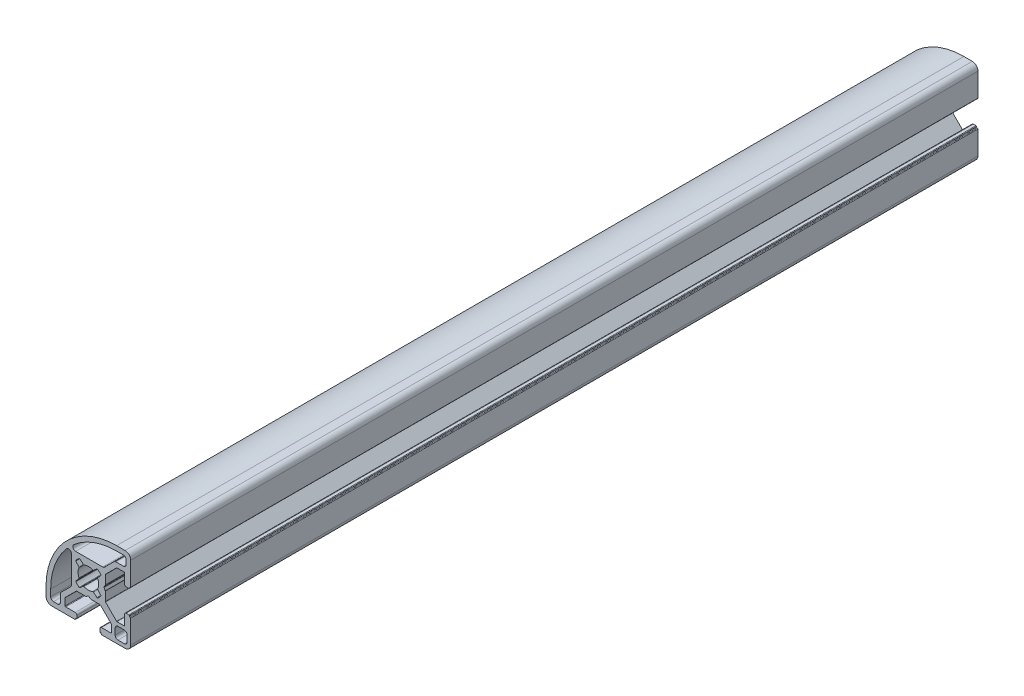
SolidWorks part; units mm, degrees
ref_plane "Front Plane" through (0, 0, 0) normal (0, 0, 1) x (1, 0, 0)
ref_plane "Top Plane" through (0, 0, 0) normal (0, 1, 0) x (1, 0, 0)
ref_plane "Right Plane" through (0, 0, 0) normal (1, 0, 0) x (0, 0, -1)
sketch "Sketch1" plane through (0, 0, 0) normal (0, 0, 1) x (1, 0, 0)
  line L0 (-5.9955, -5.0479) -> (-5.9955, 4.5146)
  line L1 (-9.6071, -9.0737) -> (-6.2884, -5.755)
  line L2 (-9.9, -12.35) -> (-9.9, -9.7808)
  line L3 (-13.35, -12.35) -> (-13.35, -10)
  line L4 (-10.9, -13.35) -> (-12.35, -13.35)
  line L5 (13.35, 10.9) -> (13.35, 12.35)
  line L6 (12.35, 13.35) -> (10, 13.35)
  line L7 (12.35, 9.9) -> (9.7808, 9.9)
  line L8 (9.0737, 9.6071) -> (5.755, 6.2884)
  line L9 (5.0479, 5.9955) -> (-4.5146, 5.9955)
  line L10 (13.7, -10.5) -> (13.7, -12.7)
  line L11 (5.9777, -0.8536) -> (5.5426, -0.1)
  line L12 (5.9777, 0.8536) -> (5.5426, 0.1)
  line L13 (6.0045, -4.1216) -> (6.0045, -0.9536)
  line L14 (6.0045, 4.1216) -> (6.0045, 0.9536)
  line L15 (-3.3344, 1.7592) -> (-4.4052, 3.0354)
  line L16 (-1.7592, 3.3344) -> (-3.0354, 4.4052)
  line L17 (1.7592, 3.3344) -> (3.0354, 4.4052)
  line L18 (3.3344, 1.7592) -> (4.4052, 3.0354)
  line L19 (15, 4.75) -> (15, 13)
  line L20 (13, 15) -> (10, 15)
  line L21 (14.5, 4.35) -> (14.5, 4.25)
  line L22 (14.3, 4.05) -> (13.4, 4.05)
  line L23 (12.8, 4.65) -> (12.8, 8.05)
  line L24 (14.7, 4.55) -> (14.8, 4.55)
  line L25 (12.6, 8.25) -> (10.1328, 8.25)
  line L26 (9.9914, 8.1914) -> (6.063, 4.263)
  line L27 (8.1914, -9.9914) -> (4.263, -6.063)
  line L28 (8.25, -12.6) -> (8.25, -10.1328)
  line L29 (9.9914, -8.1914) -> (6.063, -4.263)
  line L30 (12.6, -8.25) -> (10.1328, -8.25)
  line L31 (14.7, -4.55) -> (14.8, -4.55)
  line L32 (12.8, -4.65) -> (12.8, -8.05)
  line L33 (14.3, -4.05) -> (13.4, -4.05)
  line L34 (14.5, -4.35) -> (14.5, -4.25)
  line L35 (4.65, -12.8) -> (8.05, -12.8)
  line L36 (4.05, -14.3) -> (4.05, -13.4)
  line L37 (4.35, -14.5) -> (4.25, -14.5)
  line L38 (4.55, -14.8) -> (4.55, -14.7)
  line L39 (13, -15) -> (4.75, -15)
  line L40 (15, -4.75) -> (15, -13)
  line L41 (3.3344, -1.7592) -> (4.4052, -3.0354)
  line L42 (1.7592, -3.3344) -> (3.0354, -4.4052)
  line L43 (-1.7592, -3.3344) -> (-3.0354, -4.4052)
  line L44 (-3.3344, -1.7592) -> (-4.4052, -3.0354)
  line L45 (-15, -10) -> (-15, -13)
  line L46 (-13, -15) -> (-4.75, -15)
  line L47 (-4.55, -14.8) -> (-4.55, -14.7)
  line L48 (-4.35, -14.5) -> (-4.25, -14.5)
  line L49 (-4.05, -14.3) -> (-4.05, -13.4)
  line L50 (-4.65, -12.8) -> (-8.05, -12.8)
  line L51 (-8.1914, -9.9914) -> (-4.263, -6.063)
  line L52 (-4.1216, -6.0045) -> (-0.9536, -6.0045)
  line L53 (-0.8536, -5.9777) -> (-0.1, -5.5426)
  line L54 (12.7, -9.5) -> (10.5, -9.5)
  line L55 (9.5, -10.5) -> (9.5, -12.7)
  line L56 (10.5, -13.7) -> (12.7, -13.7)
  line L57 (0.8536, -5.9777) -> (0.1, -5.5426)
  line L58 (4.1216, -6.0045) -> (0.9536, -6.0045)
  line L59 (-8.25, -12.6) -> (-8.25, -10.1328)
  arc A0 (-5.9955, 4.5146) -> (-7.756, 5.164) centre (-6.9955, 4.5146) ccw
  arc A1 (-6.2884, -5.755) -> (-5.9955, -5.0479) centre (-6.9955, -5.0479) ccw
  arc A2 (-7.756, 5.164) -> (-13.35, -10) centre (10, -10) ccw
  arc A3 (-13.35, -12.35) -> (-12.35, -13.35) centre (-12.35, -12.35) ccw
  arc A4 (-10.9, -13.35) -> (-9.9, -12.35) centre (-10.9, -12.35) ccw
  arc A5 (-9.6071, -9.0737) -> (-9.9, -9.7808) centre (-8.9, -9.7808) ccw
  arc A6 (-5.164, 7.756) -> (-4.5146, 5.9955) centre (-4.5146, 6.9955) ccw
  arc A7 (5.0479, 5.9955) -> (5.755, 6.2884) centre (5.0479, 6.9955) ccw
  arc A8 (9.7808, 9.9) -> (9.0737, 9.6071) centre (9.7808, 8.9) ccw
  arc A9 (12.35, 9.9) -> (13.35, 10.9) centre (12.35, 10.9) ccw
  arc A10 (13.35, 12.35) -> (12.35, 13.35) centre (12.35, 12.35) ccw
  arc A11 (10, 13.35) -> (-5.164, 7.756) centre (10, -10) ccw
  arc A12 (-8.1914, -9.9914) -> (-8.25, -10.1328) centre (-8.05, -10.1328) ccw
  arc A13 (-4.1216, -6.0045) -> (-4.263, -6.063) centre (-4.1216, -6.2045) ccw
  arc A14 (-0.9536, -6.0045) -> (-0.8536, -5.9777) centre (-0.9536, -5.8045) ccw
  arc A15 (0.8536, -5.9777) -> (0.9536, -6.0045) centre (0.9536, -5.8045) ccw
  arc A16 (4.263, -6.063) -> (4.1216, -6.0045) centre (4.1216, -6.2045) ccw
  arc A17 (8.25, -10.1328) -> (8.1914, -9.9914) centre (8.05, -10.1328) ccw
  arc A18 (5.9777, 0.8536) -> (6.0045, 0.9536) centre (5.8045, 0.9536) ccw
  arc A19 (6.0045, -0.9536) -> (5.9777, -0.8536) centre (5.8045, -0.9536) ccw
  arc A20 (9.9914, -8.1914) -> (10.1328, -8.25) centre (10.1328, -8.05) ccw
  arc A21 (6.0045, -4.1216) -> (6.063, -4.263) centre (6.2045, -4.1216) ccw
  arc A22 (10.1328, 8.25) -> (9.9914, 8.1914) centre (10.1328, 8.05) ccw
  arc A23 (6.063, 4.263) -> (6.0045, 4.1216) centre (6.2045, 4.1216) ccw
  arc A24 (3.2833, 4.4125) -> (3.0354, 4.4052) centre (3.1639, 4.252) ccw
  arc A25 (4.4052, 3.0354) -> (4.4125, 3.2833) centre (4.252, 3.1639) ccw
  arc A26 (4.4125, -3.2833) -> (4.4052, -3.0354) centre (4.252, -3.1639) ccw
  arc A27 (3.0354, -4.4052) -> (3.2833, -4.4125) centre (3.1639, -4.252) ccw
  arc A28 (-3.2833, -4.4125) -> (-3.0354, -4.4052) centre (-3.1639, -4.252) ccw
  arc A29 (-4.4052, -3.0354) -> (-4.4125, -3.2833) centre (-4.252, -3.1639) ccw
  arc A30 (-4.4125, 3.2833) -> (-4.4052, 3.0354) centre (-4.252, 3.1639) ccw
  arc A31 (-3.0354, 4.4052) -> (-3.2833, 4.4125) centre (-3.1639, 4.252) ccw
  arc A32 (-3.3064, 1.5459) -> (-3.3344, 1.7592) centre (-3.4876, 1.6307) ccw
  arc A33 (-3.3344, -1.7592) -> (-3.3064, -1.5459) centre (-3.4876, -1.6307) ccw
  arc A34 (-1.5459, -3.3064) -> (-1.7592, -3.3344) centre (-1.6307, -3.4876) ccw
  arc A35 (1.7592, -3.3344) -> (1.5459, -3.3064) centre (1.6307, -3.4876) ccw
  arc A36 (3.3064, -1.5459) -> (3.3344, -1.7592) centre (3.4876, -1.6307) ccw
  arc A37 (3.3344, 1.7592) -> (3.3064, 1.5459) centre (3.4876, 1.6307) ccw
  arc A38 (1.5459, 3.3064) -> (1.7592, 3.3344) centre (1.6307, 3.4876) ccw
  arc A39 (-1.7592, 3.3344) -> (-1.5459, 3.3064) centre (-1.6307, 3.4876) ccw
  arc A40 (-1.5459, -3.3064) -> (1.5459, -3.3064) centre (0, 0) ccw
  arc A41 (-3.3064, 1.5459) -> (-3.3064, -1.5459) centre (0, 0) ccw
  arc A42 (1.5459, 3.3064) -> (-1.5459, 3.3064) centre (0, 0) ccw
  arc A43 (3.3064, -1.5459) -> (3.3064, 1.5459) centre (0, 0) ccw
  arc A44 (10, 15) -> (-15, -10) centre (10, -10) ccw
  arc A45 (5.5426, 0.1) -> (5.5426, -0.1) centre (5.7158, 0) ccw
  arc A46 (12.8, 4.65) -> (13.4, 4.05) centre (13.4, 4.65) ccw
  arc A47 (-4.05, -13.4) -> (-4.65, -12.8) centre (-4.65, -13.4) ccw
  arc A48 (4.65, -12.8) -> (4.05, -13.4) centre (4.65, -13.4) ccw
  arc A49 (13.4, -4.05) -> (12.8, -4.65) centre (13.4, -4.65) ccw
  arc A50 (-3.2833, 4.4125) -> (-4.4125, 3.2833) centre (0, 0) ccw
  arc A51 (4.4125, 3.2833) -> (3.2833, 4.4125) centre (0, 0) ccw
  arc A52 (12.8, 8.05) -> (12.6, 8.25) centre (12.6, 8.05) ccw
  arc A53 (14.7, 4.55) -> (14.5, 4.35) centre (14.7, 4.35) ccw
  arc A54 (14.3, 4.05) -> (14.5, 4.25) centre (14.3, 4.25) ccw
  arc A55 (14.8, 4.55) -> (15, 4.75) centre (14.8, 4.75) ccw
  arc A56 (15, 13) -> (13, 15) centre (13, 13) ccw
  arc A57 (13, -15) -> (15, -13) centre (13, -13) ccw
  arc A58 (15, -4.75) -> (14.8, -4.55) centre (14.8, -4.75) ccw
  arc A59 (14.5, -4.25) -> (14.3, -4.05) centre (14.3, -4.25) ccw
  arc A60 (14.5, -4.35) -> (14.7, -4.55) centre (14.7, -4.35) ccw
  arc A61 (12.6, -8.25) -> (12.8, -8.05) centre (12.6, -8.05) ccw
  arc A62 (8.05, -12.8) -> (8.25, -12.6) centre (8.05, -12.6) ccw
  arc A63 (4.05, -14.3) -> (4.25, -14.5) centre (4.25, -14.3) ccw
  arc A64 (4.55, -14.8) -> (4.75, -15) centre (4.75, -14.8) ccw
  arc A65 (4.55, -14.7) -> (4.35, -14.5) centre (4.35, -14.7) ccw
  arc A66 (3.2833, -4.4125) -> (4.4125, -3.2833) centre (0, 0) ccw
  arc A67 (-4.4125, -3.2833) -> (-3.2833, -4.4125) centre (0, 0) ccw
  arc A68 (-4.35, -14.5) -> (-4.55, -14.7) centre (-4.35, -14.7) ccw
  arc A69 (-4.75, -15) -> (-4.55, -14.8) centre (-4.75, -14.8) ccw
  arc A70 (-4.25, -14.5) -> (-4.05, -14.3) centre (-4.25, -14.3) ccw
  arc A71 (-15, -13) -> (-13, -15) centre (-13, -13) ccw
  arc A72 (9.5, -12.7) -> (10.5, -13.7) centre (10.5, -12.7) ccw
  arc A73 (10.5, -9.5) -> (9.5, -10.5) centre (10.5, -10.5) ccw
  arc A74 (13.7, -10.5) -> (12.7, -9.5) centre (12.7, -10.5) ccw
  arc A75 (12.7, -13.7) -> (13.7, -12.7) centre (12.7, -12.7) ccw
  arc A76 (0.1, -5.5426) -> (-0.1, -5.5426) centre (0, -5.7158) ccw
  arc A77 (-8.25, -12.6) -> (-8.05, -12.8) centre (-8.05, -12.6) ccw
extrude "Extrude1" add sketch "Sketch1" along normal blind 300
